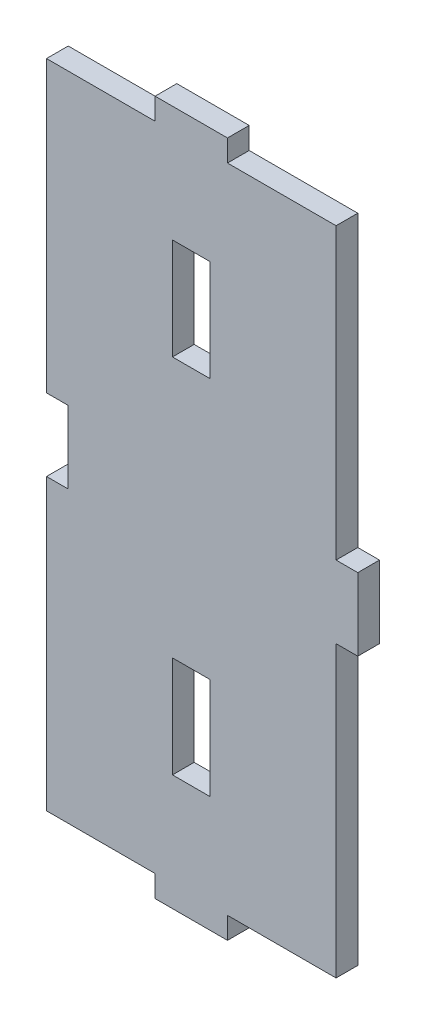
SolidWorks part; units mm, degrees
ref_plane "Front Plane" through (0, 0, 0) normal (0, 0, 1) x (1, 0, 0)
ref_plane "Top Plane" through (0, 0, 0) normal (0, 1, 0) x (1, 0, 0)
ref_plane "Right Plane" through (0, 0, 0) normal (1, 0, 0) x (0, 0, -1)
sketch "Sketch1" plane through (0, 0, 0) normal (0, 0, 1) x (1, 0, 0)
  line L0 (0, 45.197) -> (15, 45.197)
  line L1 (40, 45.197) -> (40, 5.197)
  line L2 (40, -44.803) -> (25, -44.803)
  line L3 (0, -44.803) -> (0, -4.803)
  line L4 (0, -4.803) -> (3, -4.803)
  line L5 (3, -4.803) -> (3, 5.197)
  line L6 (3, 5.197) -> (0, 5.197)
  line L7 (0, 5.197) -> (0, 45.197)
  line L8 (25, 45.197) -> (40, 45.197)
  line L10 (15, 45.197) -> (15, 48.197)
  line L11 (15, 48.197) -> (25, 48.197)
  line L12 (25, 45.197) -> (25, 48.197)
  line L13 (40, 0.197) -> (3, 0.197) construction
  line L14 (25, -44.803) -> (25, -47.803)
  line L15 (15, -47.803) -> (25, -47.803)
  line L16 (15, -44.803) -> (15, -47.803)
  line L17 (15, -44.803) -> (0, -44.803)
  line L18 (40, -4.803) -> (40, -44.803)
  line L19 (40, -4.803) -> (43, -4.803)
  line L21 (40, 5.197) -> (43, 5.197)
  line L22 (43, -4.803) -> (43, 5.197)
  line L23 (40, 0.197) -> (43, 5.197) construction
  line L24 (40, 0.197) -> (43, -4.803) construction
  line L25 (17.4, 18.197) -> (22.6, 18.197)
  line L30 (0, 25.197) -> (40, 25.197) construction
  line L31 (20, 48.197) -> (20, -47.803) construction
  line L32 (17.4, 18.197) -> (17.4, 32.197)
  line L33 (17.4, 32.197) -> (22.6, 32.197)
  line L34 (22.6, 18.197) -> (22.6, 32.197)
  line L35 (17.4, 18.197) -> (22.6, 32.197) construction
  line L36 (17.4, 32.197) -> (22.6, 18.197) construction
  line L37 (17.4, -31.803) -> (22.6, -17.803) construction
  line L38 (17.4, -17.803) -> (22.6, -31.803) construction
  line L39 (22.6, -17.803) -> (22.6, -31.803)
  line L40 (17.4, -31.803) -> (22.6, -31.803)
  line L41 (17.4, -17.803) -> (17.4, -31.803)
  line L42 (17.4, -17.803) -> (22.6, -17.803)
  point P3 (20, 45.197)
  point P6 (20, 25.197)
  point P25 (20, -44.803)
  point P33 (20, -24.803)
  dimension "D1" = 14
  dimension "D2" = 5.2
extrude "Boss-Extrude1" add sketch "Sketch1" along normal blind 3
